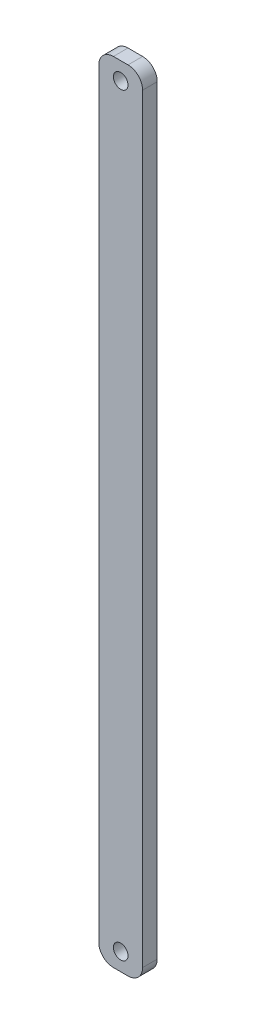
SolidWorks part; units mm, degrees
ref_plane "Front Plane" through (0, 0, 0) normal (0, 0, 1) x (1, 0, 0)
ref_plane "Top Plane" through (0, 0, 0) normal (0, 1, 0) x (1, 0, 0)
ref_plane "Right Plane" through (0, 0, 0) normal (1, 0, 0) x (0, 0, -1)
sketch "Sketch1" plane through (0, 0, 0) normal (0, 0, 1) x (1, 0, 0)
  line L0 (1.5, -27) -> (1.5, 27) construction
  line L1 (1.5, 27) -> (3, 27) construction
  line L2 (1.5, 27) -> (0, 27) construction
  line L3 (1, 27) -> (2, 27)
  line L4 (3, 26) -> (3, -26)
  line L5 (2, -27) -> (1.5, -27)
  line L6 (0, -26) -> (0, 26)
  line L7 (1, -27) -> (1.5, -27)
  arc A0 (3, -26) -> (2, -27) centre (2, -26) cw
  arc A1 (3, 26) -> (2, 27) centre (2, 26) ccw
  arc A2 (0, 26) -> (1, 27) centre (1, 26) cw
  arc A3 (0, -26) -> (1, -27) centre (1, -26) ccw
  circle A4 centre (1.5, 25.8) radius 0.5
  circle A5 centre (1.5, -25.8) radius 0.5
  point P19 (0, 0)
  dimension "D4" = 1
  dimension "D5" = 1
  dimension "D6" = 25.8
  dimension "D7" = 1
  dimension "D8" = 1
  dimension "D1" = 54
  dimension "D2" = 1.5
  dimension "D3" = 1.5
  dimension "D9" = 25.8
extrude "Boss-Extrude1" add sketch "Sketch1" along normal blind 1
